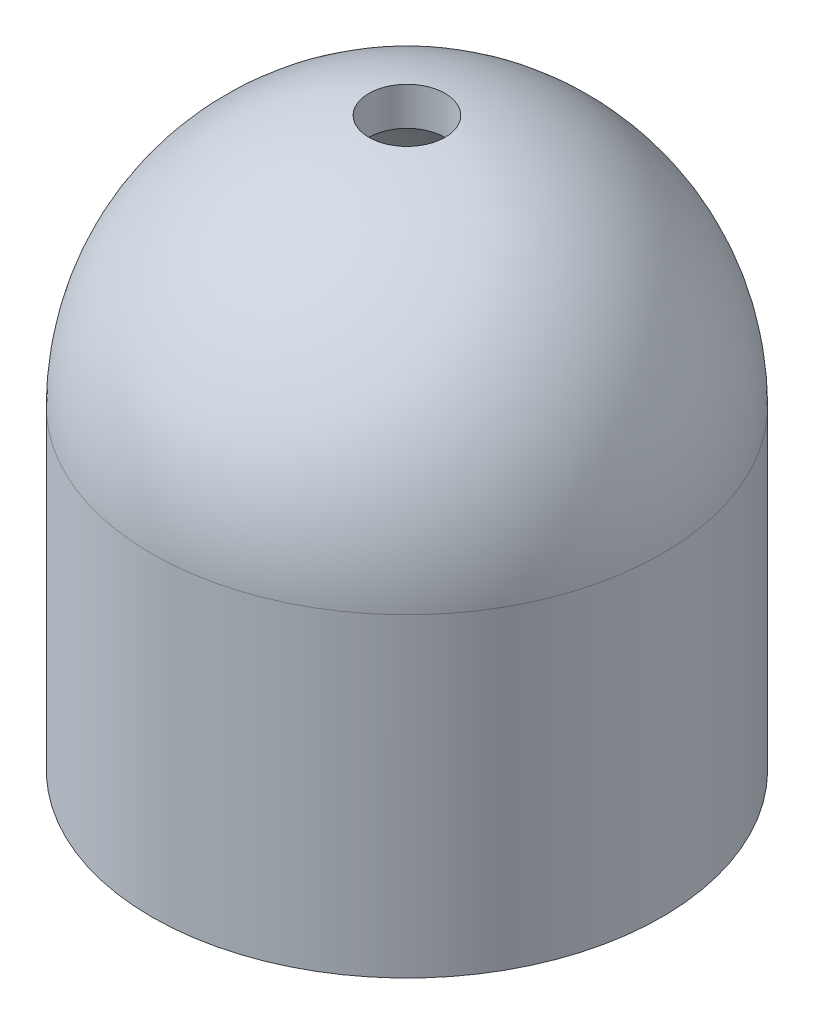
SolidWorks part; units mm, degrees
ref_plane "Front Plane" through (0, 0, 0) normal (0, 0, 1) x (1, 0, 0)
ref_plane "Top Plane" through (0, 0, 0) normal (0, 1, 0) x (1, 0, 0)
ref_plane "Right Plane" through (0, 0, 0) normal (1, 0, 0) x (0, 0, -1)
sketch "Sketch1" plane through (0, 0, 0) normal (0, 1, 0) x (1, 0, 0)
  circle A0 centre (0, 0) radius 28.2321
  circle A1 centre (0, 0) radius 24.1046
  dimension "D1" = 56.4642
  dimension "D2" = 48.2092
extrude "Boss-Extrude1" add sketch "Sketch1" against normal blind 34.8234
sketch "Sketch2" plane through (0, 0, 0) normal (0, 0, 1) x (1, 0, 0)
  line L0 (0, 35.0039) -> (0, -3.3968) construction
  line L1 (-28.2321, 0) -> (0, 0) construction
  line L2 (0, 24.0665) -> (0, 28.2321)
  line L3 (-28.2321, 0) -> (-24.0665, 0)
  arc A0 (0, 28.2321) -> (-28.2321, 0) centre (0, 0) ccw
  arc A1 (0, 24.0665) -> (-24.0665, 0) centre (0, 0) ccw
  dimension "D1" = 48.133
revolve "Revolve1" add sketch "Sketch2" angle 360 about L2
sketch "Sketch3" plane through (0, 0, 0) normal (0, 1, 0) x (1, 0, 0)
  circle A0 centre (0, 0) radius 4.2164
  dimension "D1" = 8.4328
extrude "Cut-Extrude1" cut sketch "Sketch3" along normal blind 34.8234
